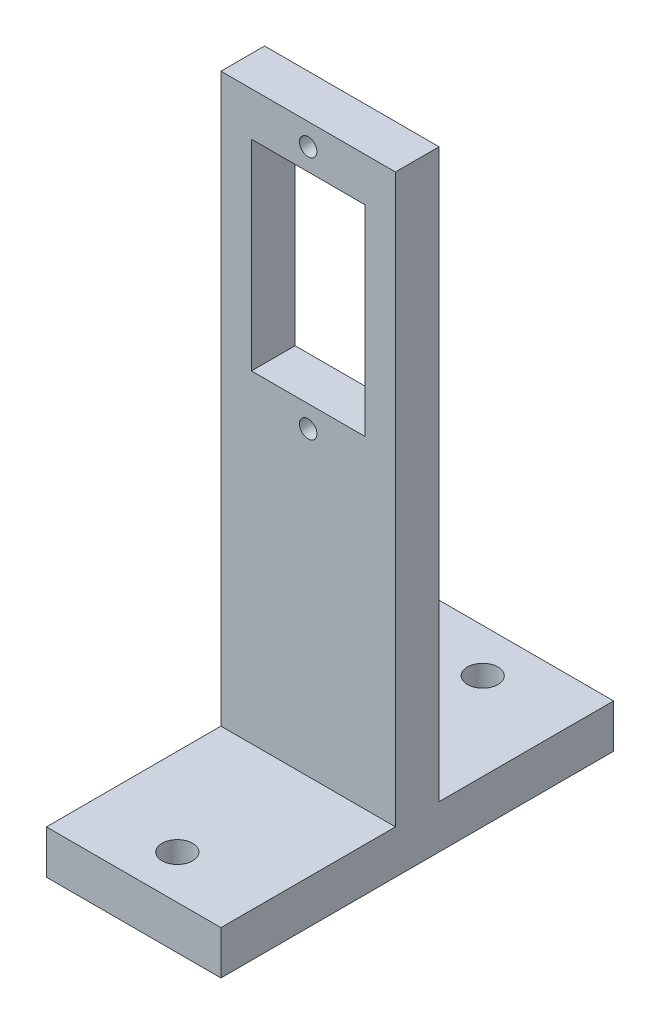
SolidWorks part; units mm, degrees
ref_plane "Ön Düzlem" through (0, 0, 0) normal (0, 0, 1) x (1, 0, 0)
ref_plane "Üst Düzlem" through (0, 0, 0) normal (0, 1, 0) x (1, 0, 0)
ref_plane "Sağ Düzlem" through (0, 0, 0) normal (1, 0, 0) x (0, 0, -1)
sketch "Çizim1" plane through (0, 0, 0) normal (0, 1, 0) x (1, 0, 0)
  line L1 (0, 0) -> (20, 0)
  line L2 (0, 0) -> (0, 5)
  line L3 (0, 5) -> (20, 5)
  line L4 (20, 0) -> (20, 5)
  dimension "D1" = 5
  dimension "D2" = 20
extrude "Yükseklik-Ekstrüzyon3" add sketch "Çizim1" along normal blind 70
sketch "Çizim2" plane through (0, 0, 0) normal (0, 0, 1) x (1, 0, 0)
  line L0 (0, 70) -> (20, 70) construction
  line L1 (3.5, 65) -> (16.5, 65)
  line L2 (3.5, 65) -> (3.5, 42)
  line L3 (3.5, 42) -> (16.5, 42)
  line L4 (16.5, 65) -> (16.5, 42)
  line L5 (20, 70) -> (20, 0) construction
  circle A0 centre (10, 67.5) radius 1
  circle A1 centre (10, 39.5) radius 1
  point P12 (0, 0)
  point P13 (0, 0)
  dimension "D5" = 2
  dimension "D7" = 2.5
  dimension "D1" = 23
  dimension "D2" = 5
  dimension "D3" = 13
  dimension "D4" = 3.5
  dimension "D6" = 2.5
  dimension "D8" = 6.5
extrude "Kes-Ekstrüzyon1" cut sketch "Çizim2" against normal blind 70
sketch "Çizim3" plane through (0, 0, 0) normal (0, 0, 1) x (1, 0, 0)
  line L0 (20, 70) -> (20, 0) construction
  line L1 (0, 0) -> (20, 0)
  line L2 (0, 0) -> (0, 5)
  line L3 (0, 5) -> (20, 5)
  line L4 (20, 0) -> (20, 5)
  dimension "D1" = 5
extrude "Yükseklik-Ekstrüzyon4" add sketch "Çizim3" against normal blind 25 and the other way blind 20
sketch "Çizim4" plane through (0, 5, 0) normal (0, 1, 0) x (1, 0, 0)
  line L0 (20, 5) -> (20, 25) construction
  line L1 (20, 25) -> (0, 25) construction
  line L2 (20, -20) -> (0, -20) construction
  circle A0 centre (10, -15) radius 1.75
  circle A1 centre (10, 20) radius 1.75
  point P4 (0, 0)
  point P11 (0, 0)
  dimension "D1" = 10
  dimension "D2" = 3.5
  dimension "D3" = 5
  dimension "D4" = 5
extrude "Kes-Ekstrüzyon2" cut sketch "Çizim4" against normal blind 25
